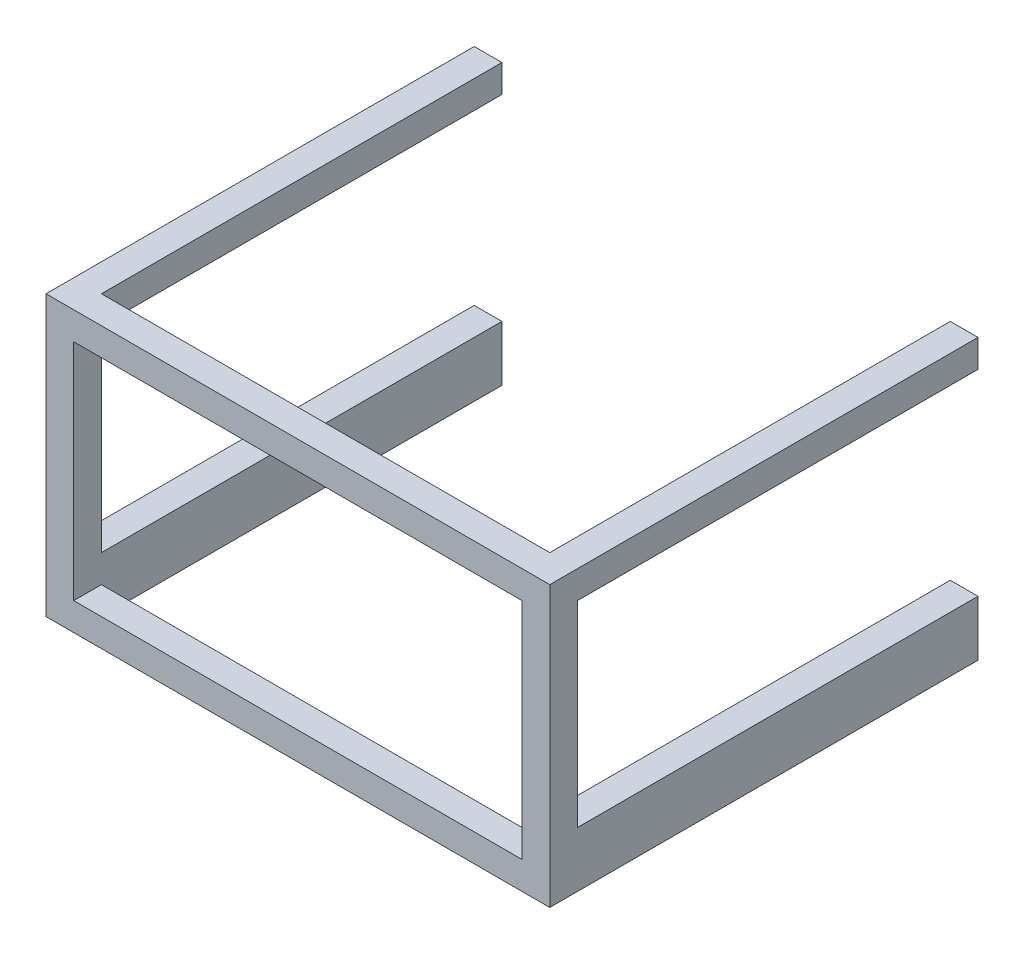
SolidWorks part; units mm, degrees
ref_plane "Plan de face" through (0, 0, 0) normal (0, 0, 1) x (1, 0, 0)
ref_plane "Plan de dessus" through (0, 0, 0) normal (0, 1, 0) x (1, 0, 0)
ref_plane "Plan de droite" through (0, 0, 0) normal (1, 0, 0) x (0, 0, -1)
sketch "Esquisse1" plane through (0, 0, 0) normal (0, 0, 1) x (1, 0, 0)
  line L1 (-180.0766, 91.5709) -> (219.9234, 91.5709)
  line L2 (-180.0766, 91.5709) -> (-180.0766, -130.4291)
  line L3 (-180.0766, -130.4291) -> (219.9234, -130.4291)
  line L4 (219.9234, 91.5709) -> (219.9234, -130.4291)
  dimension "D1" = 400
  dimension "D2" = 222
extrude "Boss.-Extru.1" add sketch "Esquisse1" along normal blind 340
sketch "Esquisse2" plane through (0, -130.4291, 0) normal (0, -1, 0) x (1, 0, 0)
  line L0 (-180.0766, 340) -> (219.9234, 340) construction
  line L1 (-158.0766, 318) -> (197.9234, 318)
  line L2 (-158.0766, 318) -> (-158.0766, 0)
  line L3 (-158.0766, 0) -> (197.9234, 0)
  line L4 (197.9234, 318) -> (197.9234, 0)
  line L6 (219.9234, 340) -> (219.9234, 0) construction
  line L7 (-180.0766, 340) -> (-180.0766, 0) construction
  line L8 (-180.0766, 0) -> (219.9234, 0) construction
  dimension "D1" = 22
  dimension "D2" = 0
  dimension "D3" = 22
  dimension "D4" = 22
extrude "Enlèv. mat.-Extru.1" cut sketch "Esquisse2" against normal through all
sketch "Esquisse8" plane through (219.9234, 0, 0) normal (1, 0, 0) x (0, 0, -1)
  line L0 (0, -130.4291) -> (0, 91.5709) construction
  line L1 (-318, 69.5709) -> (0, 69.5709)
  line L2 (-318, 69.5709) -> (-318, -86.4291)
  line L3 (-318, -86.4291) -> (0, -86.4291)
  line L4 (0, 69.5709) -> (0, -86.4291)
  line L5 (-340, 91.5709) -> (0, 91.5709) construction
  line L6 (-340, -130.4291) -> (0, -130.4291) construction
  line L7 (-340, -130.4291) -> (-340, 91.5709) construction
  dimension "D1" = 22
  dimension "D2" = 44
  dimension "D3" = 22
extrude "Enlèv. mat.-Extru.2" cut sketch "Esquisse8" against normal through all
sketch "Esquisse9" plane through (0, 0, 340) normal (0, 0, 1) x (1, 0, 0)
  line L0 (219.9234, 91.5709) -> (-180.0766, 91.5709) construction
  line L1 (-158.0766, 69.5709) -> (197.9234, 69.5709)
  line L2 (-158.0766, 69.5709) -> (-158.0766, -108.4291)
  line L3 (-158.0766, -108.4291) -> (197.9234, -108.4291)
  line L4 (197.9234, 69.5709) -> (197.9234, -108.4291)
  line L5 (219.9234, -130.4291) -> (219.9234, 91.5709) construction
  line L6 (-180.0766, -130.4291) -> (219.9234, -130.4291) construction
  line L7 (-180.0766, 91.5709) -> (-180.0766, -130.4291) construction
  dimension "D1" = 22
  dimension "D2" = 22
  dimension "D3" = 22
  dimension "D4" = 22
extrude "Enlèv. mat.-Extru.3" cut sketch "Esquisse9" against normal through all
